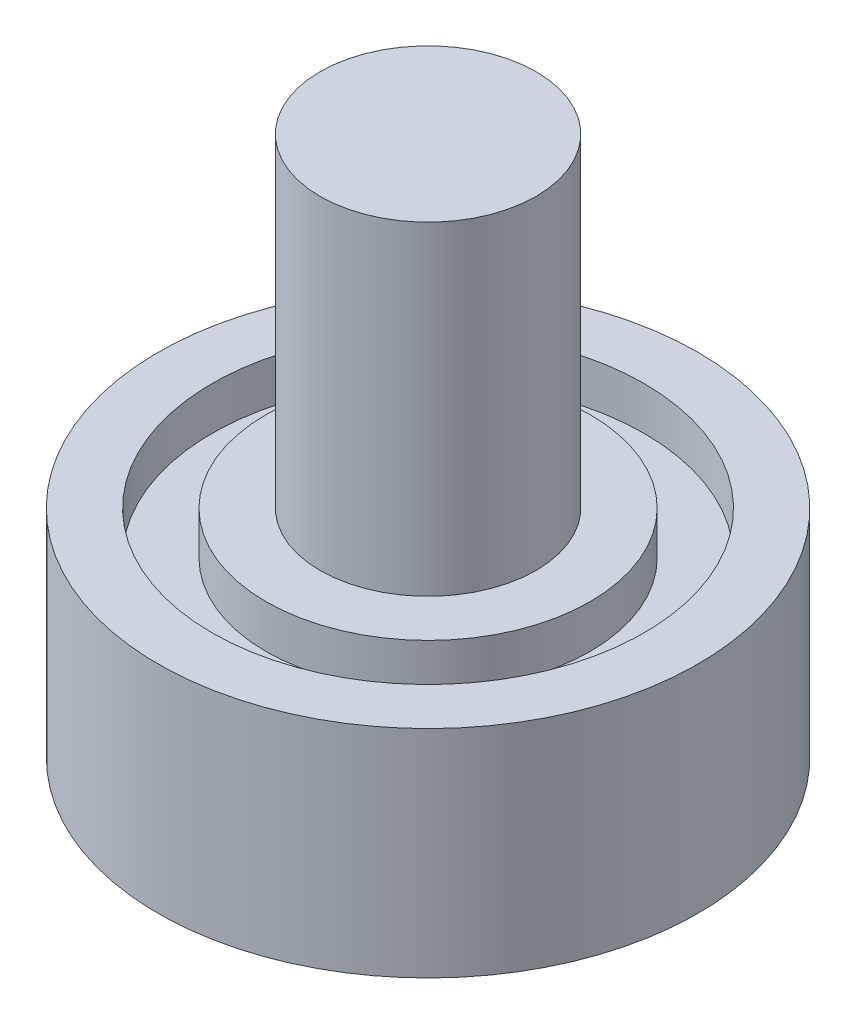
SolidWorks part; units mm, degrees
ref_plane "Front Plane" through (0, 0, 0) normal (0, 0, 1) x (1, 0, 0)
ref_plane "Top Plane" through (0, 0, 0) normal (0, 1, 0) x (1, 0, 0)
ref_plane "Right Plane" through (0, 0, 0) normal (1, 0, 0) x (0, 0, -1)
sketch "Sketch1" plane through (0, 0, 0) normal (0, 0, 1) x (1, 0, 0)
  line L0 (0, 18) -> (0, 0) construction
  line L1 (0, 0) -> (2.5, 0)
  line L2 (2.5, 0) -> (2.5, 4)
  line L3 (2.5, 4) -> (7.5, 4)
  line L4 (7.5, 4) -> (7.5, 6)
  line L5 (7.5, 6) -> (10, 6)
  line L6 (10, 6) -> (10, 4)
  line L7 (10, 4) -> (12.4977, 4)
  line L16 (0, 9) -> (12.4977, 9) construction
  line L17 (12.4977, 4) -> (12.4977, 14)
  line L18 (10, 14) -> (12.4977, 14)
  line L19 (10, 12) -> (10, 14)
  line L20 (7.5, 12) -> (10, 12)
  line L21 (7.5, 14) -> (7.5, 12)
  line L22 (7.5, 14) -> (5, 14)
  line L23 (5, 14) -> (5, 29)
  line L26 (0, 0) -> (0, 29)
  line L27 (0, 29) -> (5, 29)
  point P19 (5, 23.1824)
  point P24 (0, 9)
  dimension "D1" = 15
  dimension "D2" = 20
  dimension "D3" = 2
  dimension "D4" = 5
  dimension "D5" = 5
  dimension "D6" = 4
  dimension "D7" = 12.4977
  dimension "D8" = 15
  dimension "D9" = 5
revolve "Revolve1" add sketch "Sketch1" angle 360 about L26
sketch "Sketch2" plane through (0, 4, 0) normal (0, -1, 0) x (1, 0, 0)
  circle A0 centre (0, 0) radius 3
  dimension "D1" = 6
extrude "Boss-Extrude1" add sketch "Sketch2" along normal blind 1
